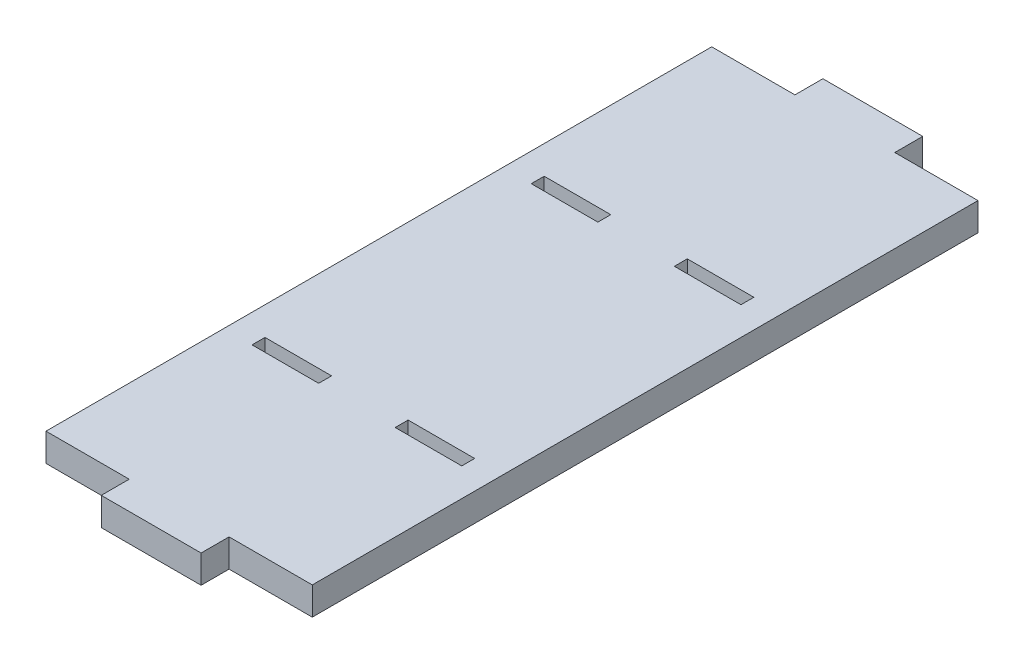
SolidWorks part; units mm, degrees
ref_plane "Front Plane" through (0, 0, 0) normal (0, 0, 1) x (1, 0, 0)
ref_plane "Top Plane" through (0, 0, 0) normal (0, 1, 0) x (1, 0, 0)
ref_plane "Right Plane" through (0, 0, 0) normal (1, 0, 0) x (0, 0, -1)
sketch "Sketch2" plane through (0, 0, 0) normal (0, 1, 0) x (1, 0, 0)
  line L1 (0, 0) -> (50.8, 0)
  line L2 (0, 0) -> (0, 127)
  line L3 (0, 127) -> (50.8, 127)
  line L4 (50.8, 0) -> (50.8, 127)
  dimension "D1" = 50.8
  dimension "D2" = 127
extrude "Base" add sketch "Sketch2" along normal blind 5.334
sketch "Sketch3" plane through (0, 0, 0) normal (0, 0, 1) x (1, 0, 0)
  line L0 (0, 0) -> (50.8, 0) construction
  line L1 (15.875, 0) -> (34.925, 0)
  line L2 (15.875, 0) -> (15.875, 5.334)
  line L3 (15.875, 5.334) -> (34.925, 5.334)
  line L4 (34.925, 0) -> (34.925, 5.334)
  line L5 (0, 5.334) -> (50.8, 5.334) construction
  line L6 (15.875, 2.667) -> (0, 2.667) construction
  line L7 (0, 5.334) -> (0, 0) construction
  line L8 (34.925, 2.667) -> (50.8, 2.667) construction
  line L9 (50.8, 5.334) -> (50.8, 0) construction
  dimension "D1" = 19.05
extrude "Tabs" add sketch "Sketch3" along normal blind 5.334
ref_plane "Mirror Plane" through (0, 0, -63.5) normal (0, 0, 1) x (1, 0, 0)
mirror "Tabs Mirror" about plane through (0, 0, -63.5) normal (0, 0, 1) of "Tabs"
sketch "Sketch4" plane through (0, 0, 0) normal (0, -1, 0) x (1, 0, 0)
  line L0 (5.4, -33.9136) -> (5.4, -36.3774) construction
  line L1 (5.4, -36.3774) -> (18.1, -36.3774) construction
  line L2 (18.1, -36.3774) -> (18.1, -33.9136) construction
  line L3 (18.1, -33.9136) -> (5.4, -33.9136) construction
  line L4 (45.4, -36.3774) -> (45.4, -33.9136) construction
  line L5 (45.4, -33.9136) -> (32.7, -33.9136) construction
  line L6 (32.7, -33.9136) -> (32.7, -36.3774) construction
  line L7 (32.7, -36.3774) -> (45.4, -36.3774) construction
  line L8 (5.4, -87.1774) -> (5.4, -89.6412) construction
  line L9 (5.4, -89.6412) -> (18.1, -89.6412) construction
  line L10 (18.1, -89.6412) -> (18.1, -87.1774) construction
  line L11 (18.1, -87.1774) -> (5.4, -87.1774) construction
  line L12 (45.4, -89.6412) -> (45.4, -87.1774) construction
  line L13 (45.4, -87.1774) -> (32.7, -87.1774) construction
  line L14 (32.7, -87.1774) -> (32.7, -89.6412) construction
  line L15 (32.7, -89.6412) -> (45.4, -89.6412) construction
  line L16 (5.4, -33.9136) -> (5.4, -36.3774)
  line L17 (5.4, -36.3774) -> (18.1, -36.3774)
  line L18 (18.1, -36.3774) -> (18.1, -33.9136)
  line L19 (18.1, -33.9136) -> (5.4, -33.9136)
  line L20 (45.4, -36.3774) -> (45.4, -33.9136)
  line L21 (45.4, -33.9136) -> (32.7, -33.9136)
  line L22 (32.7, -33.9136) -> (32.7, -36.3774)
  line L23 (32.7, -36.3774) -> (45.4, -36.3774)
  line L24 (5.4, -87.1774) -> (5.4, -89.6412)
  line L25 (5.4, -89.6412) -> (18.1, -89.6412)
  line L26 (18.1, -89.6412) -> (18.1, -87.1774)
  line L27 (18.1, -87.1774) -> (5.4, -87.1774)
  line L28 (45.4, -89.6412) -> (45.4, -87.1774)
  line L29 (45.4, -87.1774) -> (32.7, -87.1774)
  line L30 (32.7, -87.1774) -> (32.7, -89.6412)
  line L31 (32.7, -89.6412) -> (45.4, -89.6412)
  line L32 (0, 0) -> (15.875, 0) construction
  line L33 (15.875, -127) -> (0, -127) construction
  dimension "D1" = 33.9136
  dimension "D2" = 37.3588
extrude "Mount Points" cut sketch "Sketch4" against normal through all
equation "\"material\"= \"mdf@base.assembly\""
equation "\"D1@Base\"=\"material\""
